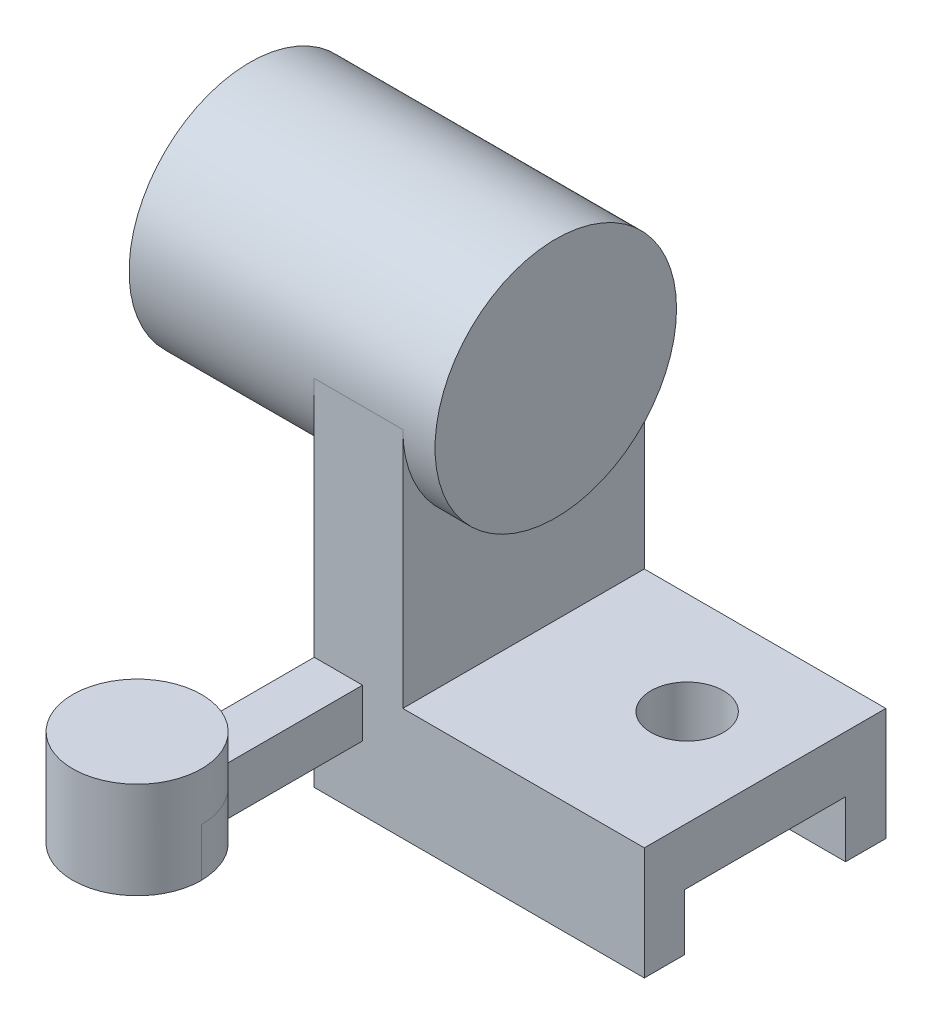
SolidWorks part; units mm, degrees
ref_plane "Front Plane" through (0, 0, 0) normal (0, 0, 1) x (1, 0, 0)
ref_plane "Top Plane" through (0, 0, 0) normal (0, 1, 0) x (1, 0, 0)
ref_plane "Right Plane" through (0, 0, 0) normal (1, 0, 0) x (0, 0, -1)
sketch "Sketch1" plane through (0, 0, 0) normal (0, 1, 0) x (1, 0, 0)
  line L1 (-27.1465, 16.1183) -> (32.8535, 16.1183)
  line L2 (-27.1465, 16.1183) -> (-27.1465, -43.8817)
  line L3 (-27.1465, -43.8817) -> (32.8535, -43.8817)
  line L4 (32.8535, 16.1183) -> (32.8535, -43.8817)
  dimension "D1" = 60
  dimension "D2" = 60
extrude "Boss-Extrude1" add sketch "Sketch1" against normal blind 28
sketch "Sketch2" plane through (32.8535, 0, 0) normal (1, 0, 0) x (0, 0, -1)
  line L0 (-43.8817, -28) -> (16.1183, -28) construction
  line L1 (-33.8817, -28) -> (6.1183, -28)
  line L2 (-33.8817, -28) -> (-33.8817, -14)
  line L3 (-33.8817, -14) -> (6.1183, -14)
  line L4 (6.1183, -28) -> (6.1183, -14)
  line L5 (-43.8817, -28) -> (-43.8817, 0) construction
  line L6 (16.1183, -28) -> (16.1183, 0) construction
  line L7 (-43.8817, 0) -> (16.1183, 0) construction
  dimension "D1" = 10
  dimension "D2" = 10
  dimension "D3" = 14
extrude "Cut-Extrude1" cut sketch "Sketch2" against normal up to next
sketch "Sketch3" plane through (0, 0, 0) normal (0, 1, 0) x (1, 0, 0)
  line L0 (8.8535, -0.2378) -> (8.8535, -18.2378) construction
  line L1 (-0.1465, -9.2378) -> (17.8535, -9.2378) construction
  line L2 (32.8535, -43.8817) -> (32.8535, 16.1183) construction
  circle A0 centre (8.8535, -9.2378) radius 9
  dimension "D1" = 18
  dimension "D2" = 24
extrude "Cut-Extrude2" cut sketch "Sketch3" against normal up to next
sketch "Sketch4" plane through (-27.1465, 0, 0) normal (-1, 0, 0) x (0, 0, 1)
  line L0 (-16.1183, 0) -> (43.8817, 0)
  line L1 (43.8817, 0) -> (43.8817, 60)
  line L2 (43.8817, 60) -> (-16.1183, 60)
  line L3 (-16.1183, 60) -> (-16.1183, 0)
  dimension "D1" = 60
extrude "Boss-Extrude2" add sketch "Sketch4" along normal blind 22 separate body
sketch "Sketch5" plane through (-49.1465, 0, 0) normal (-1, 0, 0) x (0, 0, 1)
  line L0 (-16.1183, 0) -> (-16.1183, -28)
  line L1 (-16.1183, -28) -> (-16.1183, 0) construction
  line L2 (-16.1183, -28) -> (43.8817, -28)
  line L3 (43.8817, -28) -> (43.8817, 0)
  line L4 (-16.1183, 0) -> (43.8817, 0) construction
  line L5 (-16.1183, 0) -> (43.8817, 0) construction
  line L6 (43.8817, 0) -> (-16.1183, 0)
extrude "Boss-Extrude3" add sketch "Sketch5" against normal blind 22
sketch "Sketch6" plane through (-27.1465, 0, 0) normal (1, 0, 0) x (0, 0, -1)
  line L0 (-43.8817, 60) -> (16.1183, 60) construction
  circle A0 centre (-13.8817, 60) radius 30
extrude "Boss-Extrude5" add sketch "Sketch6" against normal blind 68
sketch "Sketch8" plane through (-27.1465, 0, 0) normal (1, 0, 0) x (0, 0, -1)
  line L0 (-43.8817, 60) -> (16.1183, 60) construction
  circle A0 centre (-13.8817, 60) radius 30
  dimension "D1" = 60
extrude "Boss-Extrude6" add sketch "Sketch8" along normal blind 8
sketch "Sketch9" plane through (0, 0, 43.8817) normal (0, 0, 1) x (1, 0, 0)
  line L0 (-49.1465, 0) -> (-37.1465, 0)
  line L1 (-49.1465, -28) -> (-49.1465, 60) construction
  line L2 (-37.1465, 0) -> (-37.1465, -12)
  line L3 (-37.1465, -12) -> (-49.1465, -12)
  line L4 (-49.1465, -12) -> (-49.1465, 0)
  line L5 (-49.1465, -28) -> (32.8535, -28) construction
  dimension "D1" = 12
  dimension "D2" = 12
  dimension "D3" = 16
extrude "Boss-Extrude8" add sketch "Sketch9" along normal blind 50
sketch "Sketch10" plane through (0, 0, 0) normal (0, 1, 0) x (1, 0, 0)
  line L0 (-37.1465, -93.8817) -> (-49.1465, -93.8817) construction
  circle A0 centre (-43.1465, -93.8817) radius 16
  dimension "D1" = 32
extrude "Boss-Extrude9" add sketch "Sketch10" along normal blind 12
sketch "Sketch11" plane through (0, 0, 0) normal (0, -1, 0) x (1, 0, 0)
  line L0 (-59.1465, 93.8817) -> (-27.1465, 93.8817) construction
  arc A0 (-37.1465, 79.0494) -> (-49.1465, 79.0494) centre (-43.1465, 93.8817) ccw construction
  line M2 (-49.1465, 93.8817) -> (-37.1465, 93.8817)
  arc M4 (-37.1465, 79.0494) -> (-49.1465, 79.0494) centre (-43.1465, 93.8817) ccw
extrude "Boss-Extrude10" add sketch "Sketch11" along normal blind 12 contours L0 M4 M2
sketch "Sketch12" plane through (0, 0, 0) normal (0, -1, 0) x (1, 0, 0)
  line L0 (-27.1465, 93.8817) -> (-37.1465, 93.8817)
  line L1 (-37.1465, 93.8817) -> (-37.1465, 79.0494)
  arc A0 (-37.1465, 79.0494) -> (-27.1465, 93.8817) centre (-43.1465, 93.8817) ccw construction
  spline S0 degree 2 poles (-27.1465, 93.8817) (-27.6135, 83.4094) (-37.1465, 79.0494) knots 0 0 0 1 1 1
extrude "Boss-Extrude11" add sketch "Sketch12" along normal blind 12
sketch "Sketch13" plane through (0, 0, 0) normal (0, -1, 0) x (1, 0, 0)
  line L0 (-59.1465, 93.8817) -> (-49.1465, 93.8817)
  line L1 (-49.1465, 93.8817) -> (-49.1465, 79.0494)
  arc A0 (-59.1465, 93.8817) -> (-49.1465, 79.0494) centre (-43.1465, 93.8817) ccw construction
  spline S0 degree 2 poles (-59.1465, 93.8817) (-58.6795, 83.4094) (-49.1465, 79.0494) knots 0 0 0 1 1 1
extrude "Boss-Extrude12" add sketch "Sketch13" along normal blind 12
